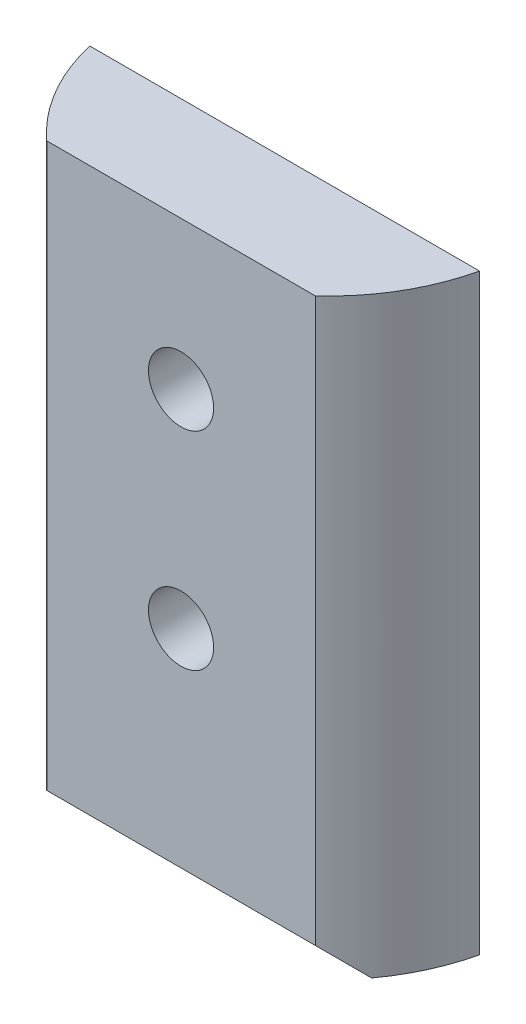
SolidWorks part; units mm, degrees
ref_plane "前视基准面" through (0, 0, 0) normal (0, 0, 1) x (1, 0, 0)
ref_plane "上视基准面" through (0, 0, 0) normal (0, 1, 0) x (1, 0, 0)
ref_plane "右视基准面" through (0, 0, 0) normal (1, 0, 0) x (0, 0, -1)
other "Configuration Table"
sketch "草图2" plane through (0, 0, 0) normal (0, 1, 0) x (1, 0, 0)
  line L0 (-6.5812, -1.5) -> (6.5812, -1.5)
  line L1 (-6.75, 0) -> (6.75, 0)
  line L2 (-4.5346, -5) -> (4.5346, -5)
  circle A0 centre (0, 0) radius 6.75
  dimension "D1" = 13.5
  dimension "D2" = 3.5
  dimension "D3" = 1.5
extrude "凸台-拉伸1" add sketch "草图2" along normal blind 20 contours L2 A0 L0
sketch "草图3" plane through (0, 0, 5) normal (0, 0, 1) x (1, 0, 0)
  line L0 (-4.5346, 0) -> (4.5346, 0) construction
  circle A0 centre (0, 15) radius 1.1
  circle A1 centre (0, 8) radius 1.1
  dimension "D3" = 2.2
  dimension "D1" = 15
  dimension "D2" = 8
extrude "切除-拉伸1" cut sketch "草图3" against normal blind 20
chamfer "倒角1" distance 1 angle 45 1 edges at (0, 0, 5)
